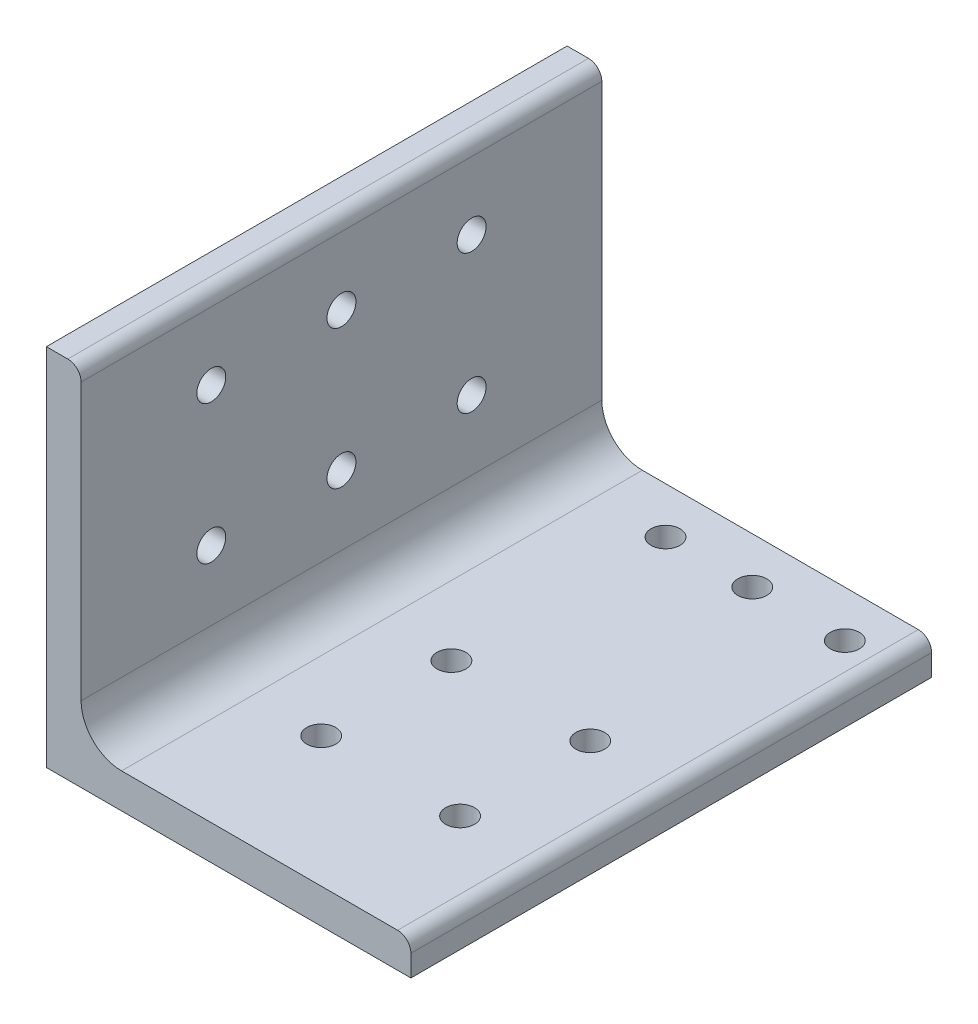
SolidWorks part; units mm, degrees
material "Сталь 3 ГОСТ 535-88"
ref_plane "Front Plane" through (0, 0, 0) normal (0, 0, 1) x (1, 0, 0)
ref_plane "Top Plane" through (0, 0, 0) normal (0, 1, 0) x (1, 0, 0)
ref_plane "Right Plane" through (0, 0, 0) normal (1, 0, 0) x (0, 0, -1)
sketch "Skizze2" plane through (0, 0, 0) normal (0, 0, 1) x (1, 0, 0)
  line L0 (0, 0) -> (63, 0)
  line L1 (0, 0) -> (0, 63)
  line L2 (0, 63) -> (3.7, 63)
  line L3 (6, 60.7) -> (6, 13)
  line L4 (0, 0) -> (63, 0)
  line L5 (13, 6) -> (60.7, 6)
  line L6 (63, 0) -> (63, 3.7)
  arc A2 (63, 3.7) -> (60.7, 6) centre (60.7, 3.7) ccw
  arc A3 (6, 60.7) -> (3.7, 63) centre (3.7, 60.7) ccw
  arc A4 (6, 13) -> (13, 6) centre (13, 13) ccw
extrude "Aufsatz-Linear austragen1" add sketch "Skizze2" along normal blind 90 contours A4 L3 A3 L2 L1 L0 L6 A2 L5
sketch "Skizze3" plane through (6, 0, 0) normal (1, 0, 0) x (0, 0, -1)
  line L4 (-67.5, 49) -> (-22.5, 49)
  line L5 (-67.5, 25) -> (-22.5, 25)
  line L6 (-45, 49) -> (-45, 25)
  line L7 (-90, 0) -> (0, 0) construction
  line L12 (-90, 0) -> (0, 0)
  line L14 (-41.374, 0) -> (-41.374, 25)
  line L15 (-90, 63) -> (0, 63) construction
  line L18 (-90, 63) -> (0, 63)
  line L19 (-38.9248, 63) -> (-38.9248, 49)
  point P5 (-45, 37)
  point P7 (-45, 25)
  point P8 (-45, 49)
  point P17 (-22.5, 36.85)
  point P18 (-67.5, 36.85)
  point P24 (-67.5, 49)
  point P25 (-22.5, 49)
  point P26 (-22.5, 25)
  point P27 (-67.5, 25)
hole_wizard "Ø5.0 (5) Durchmesser Bohrung1" positions "3D-Skizze2" profile "Skizze5" hole size "Ø5.0" standard "DIN" end condition through all
sketch3d "3D-Skizze2"
  point P0 (6, 25, 67.5)
  point P3 (6, 49, 67.5)
  point P6 (6, 49, 45)
  point P9 (6, 25, 45)
  point P12 (6, 25, 22.5)
  point P15 (6, 49, 22.5)
sketch "Skizze5" plane through (6, 25, 67.5) normal (0, 1, 0) x (0, 0, -1)
  line L0 (0, 0) -> (0, 6)
  line L1 (0, 6) -> (2.5, 6)
  line L2 (2.5, 6) -> (2.5, 0)
  line L5 (2.5, 0) -> (0, 0)
  line L11 (0, -6.35) -> (0, 107.95) construction
  dimension "Bohrerdurchmesser" = 5
  dimension "Bohrungstiefe" = 6
sketch "Skizze6" plane through (0, 6, 0) normal (0, 1, 0) x (1, 0, 0)
  line L0 (60.7, -45) -> (13, -45)
  line L1 (36.85, -45) -> (36.85, 0)
  line L2 (36.85, -45) -> (36.85, -90)
  line L3 (36.85, -67.5) -> (60.7, -67.5)
  line L4 (0, -90) -> (0, 0) construction
  line L5 (0, -90) -> (0, 0)
  line L6 (63, -90) -> (63, 0) construction
  line L7 (63, -90) -> (63, 0)
  line L8 (60.7, 0) -> (13, 0)
  line L9 (13, 0) -> (13, -89.25)
  line L10 (13, -89.25) -> (60.7, -89.25)
  line L11 (60.7, -89.25) -> (60.7, 0)
  line L12 (36.85, -22.5) -> (60.7, -22.5)
  line L13 (36.85, -22.5) -> (13, -22.5)
  line L14 (36.85, -67.5) -> (13, -67.5)
  line L15 (25, -22.5) -> (25, -67.5)
  line L16 (49, -22.5) -> (49, -67.5)
  line L17 (63, -31.8256) -> (49, -31.8256)
  line L18 (0, -37.1466) -> (25, -37.1466)
  line L19 (36.85, -8) -> (13, -8)
  line L20 (13, -16.75) -> (60.7, -16.75)
  line L21 (13, -8) -> (60.7, -8)
  line L22 (19.3849, 0) -> (19.3849, -8)
  line L23 (36.85, -8) -> (60.7, -8)
  line L24 (48.775, -8) -> (48.775, -16.75)
  line L25 (63, -7.0918) -> (48, -7.0918)
  line L26 (48, -7.0918) -> (48, -9.4032)
  line L27 (60.7, -8) -> (55.7, -8)
  line L28 (63, -4.943) -> (40, -4.943)
  line L29 (24.925, -8) -> (39.925, -8)
  line L30 (40, -4.943) -> (40, -10.8867)
  line L31 (63, -5.6635) -> (56, -5.6635)
  line L32 (56, -5.6635) -> (56, -9.8035)
  line L33 (63, -4.1211) -> (25, -4.1211)
  line L34 (25, -4.1211) -> (25, -8.3568)
  circle A0 centre (48, -8) radius 1.65
  point P19 (25, -45)
  point P20 (49, -45)
  point P21 (25, -67.5)
  point P38 (25, -8)
  point P44 (48, -8)
  point P48 (49, -67.5)
  point P61 (40, -8)
  point P62 (56, -8)
hole_wizard "Ø5.0 (5) Durchmesser Bohrung2" positions "3D-Skizze8" profile "Skizze12" hole size "Ø5.0" standard "DIN" end condition through all
sketch3d "3D-Skizze8"
  point P0 (49, 6, 67.5)
  point P3 (49, 6, 45)
  point P6 (25, 6, 45)
  point P9 (25, 6, 67.5)
  point P12 (25, 6, 8)
  point P15 (40, 6, 8)
  point P18 (56, 6, 8)
sketch "Skizze12" plane through (49, 6, 67.5) normal (1, 0, 0) x (0, 0, 1)
  line L0 (0, 0) -> (0, 6)
  line L1 (0, 6) -> (2.5, 6)
  line L2 (2.5, 6) -> (2.5, 0)
  line L5 (2.5, 0) -> (0, 0)
  line L11 (0, -6.35) -> (0, 107.95) construction
  dimension "Bohrerdurchmesser" = 5
  dimension "Bohrungstiefe" = 6
